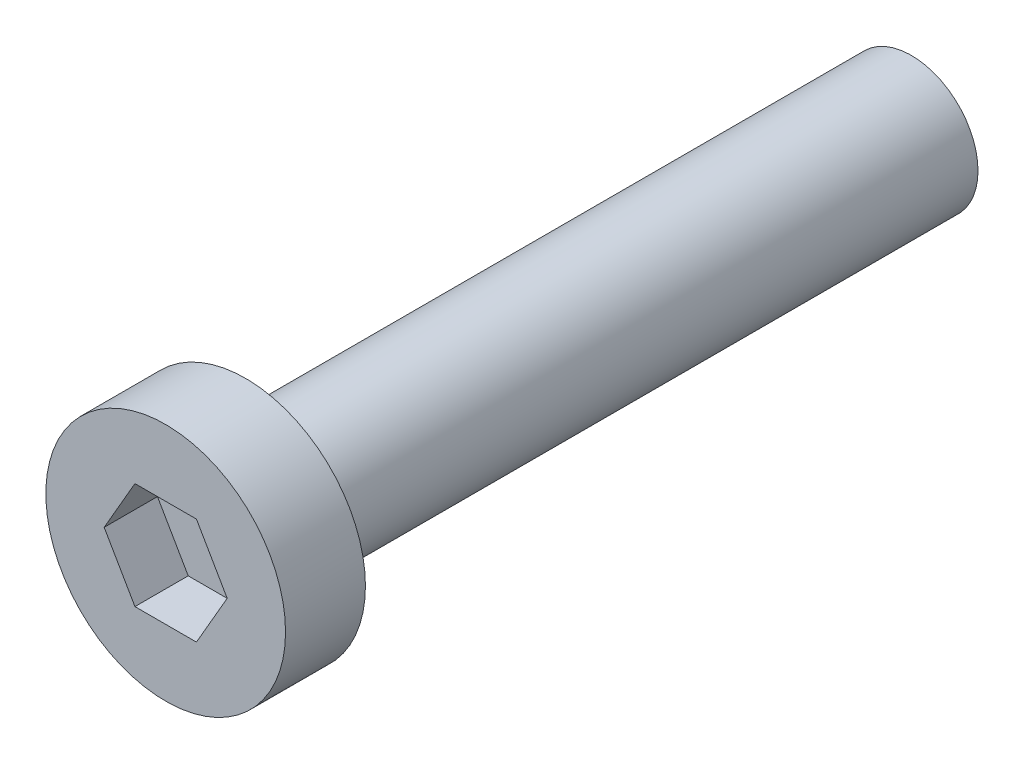
SolidWorks part; units mm, degrees
ref_plane "前视基准面" through (0, 0, 0) normal (0, 0, 1) x (1, 0, 0)
ref_plane "上视基准面" through (0, 0, 0) normal (0, 1, 0) x (1, 0, 0)
ref_plane "右视基准面" through (0, 0, 0) normal (1, 0, 0) x (0, 0, -1)
sketch "草图1" plane through (0, 0, 0) normal (0, 0, 1) x (1, 0, 0)
  circle A0 centre (0, 0) radius 5
extrude "凸台-拉伸1" add sketch "草图1" along normal blind 50
ref_plane "基准面1" through (0, 0, 50) normal (0, 0, 1) x (1, 0, 0)
sketch "草图2" plane through (0, 0, 50) normal (0, 0, 1) x (1, 0, 0)
  circle A0 centre (0, 0) radius 9
extrude "凸台-拉伸2" add sketch "草图2" along normal blind 6
ref_plane "基准面2" through (0, 0, 56) normal (0, 0, 1) x (1, 0, 0)
sketch "草图3" plane through (0, 0, 56) normal (0, 0, 1) x (1, 0, 0)
  line L0 (4.6188, 0) -> (2.3094, 4)
  line L1 (2.3094, 4) -> (-2.3094, 4)
  line L2 (-2.3094, 4) -> (-4.6188, 0)
  line L3 (-4.6188, 0) -> (-2.3094, -4)
  line L4 (-2.3094, -4) -> (2.3094, -4)
  line L5 (2.3094, -4) -> (4.6188, 0)
extrude "切除-拉伸1" cut sketch "草图3" against normal blind 4
fillet "圆角1" radius 0.5 1 edges at (5, 0, 50)
